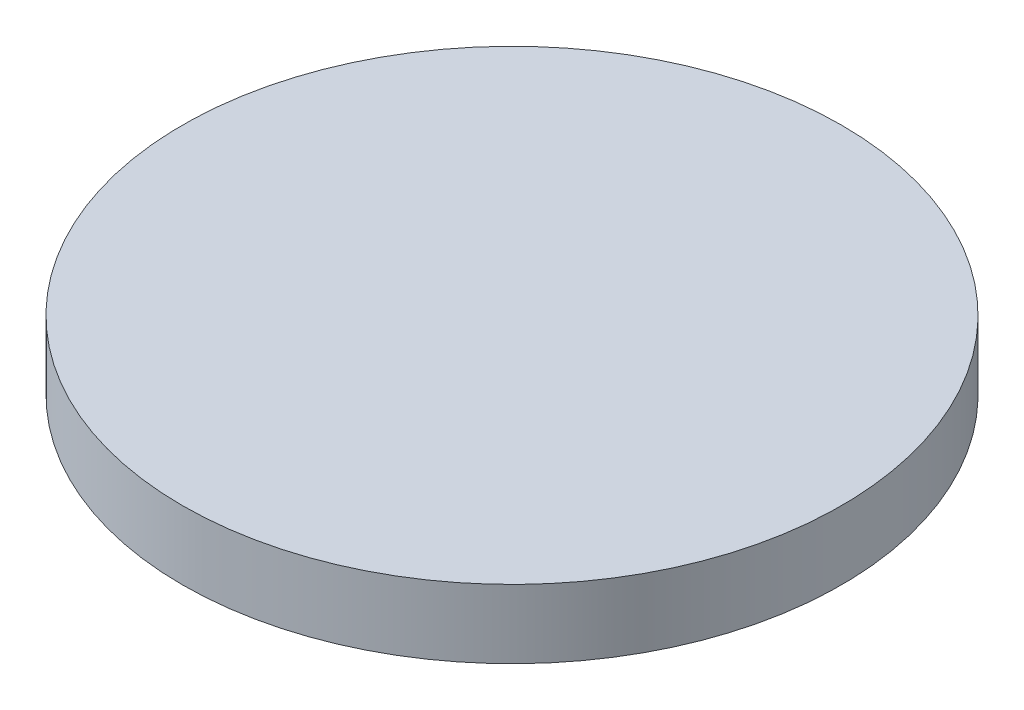
SolidWorks part; units mm, degrees
ref_plane "前视基准面" through (0, 0, 0) normal (0, 0, 1) x (1, 0, 0)
ref_plane "上视基准面" through (0, 0, 0) normal (0, 1, 0) x (1, 0, 0)
ref_plane "右视基准面" through (0, 0, 0) normal (1, 0, 0) x (0, 0, -1)
other "Configuration Table"
sketch "草图2" plane through (0, 0, 0) normal (0, 1, 0) x (1, 0, 0)
  circle A0 centre (0, 0) radius 12
extrude "凸台-拉伸1" add sketch "草图2" along normal blind 2.5
